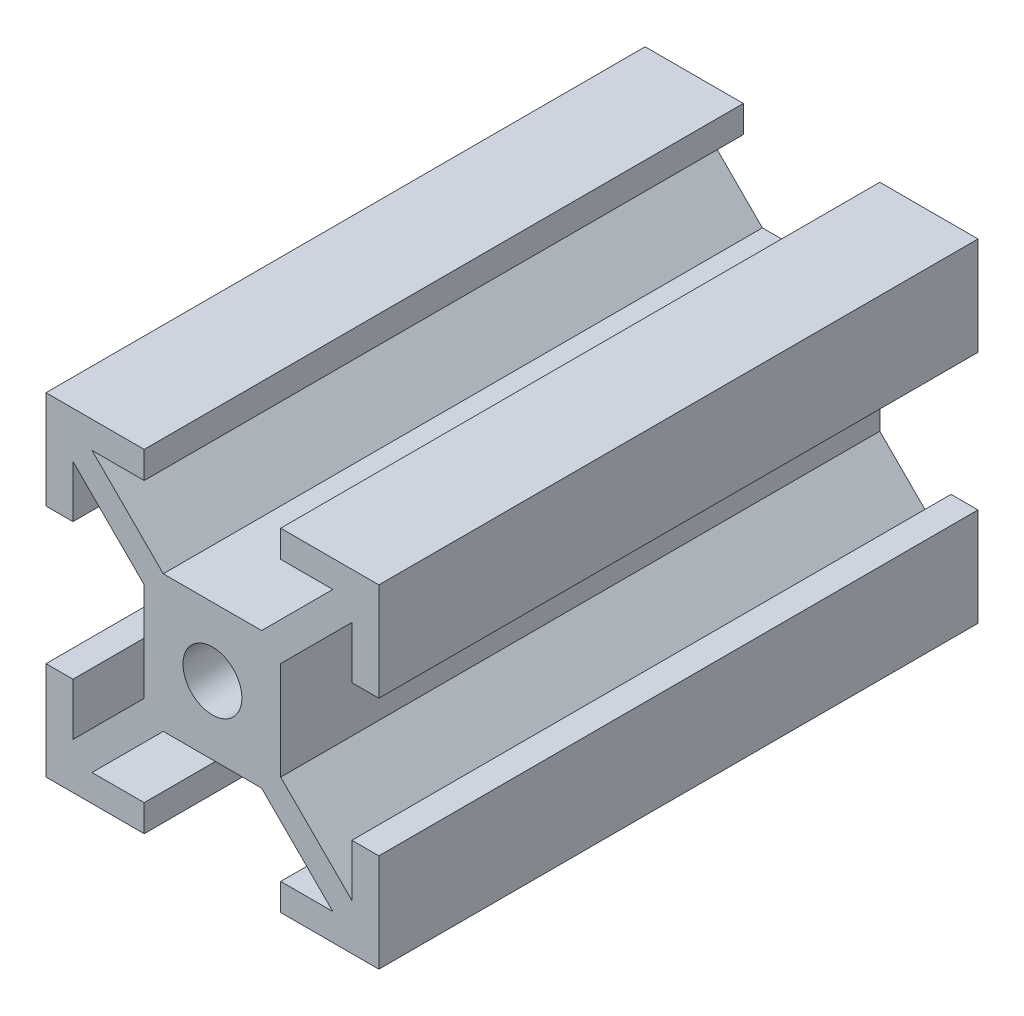
SolidWorks part; units mm, degrees
ref_plane "Front Plane" through (0, 0, 0) normal (0, 0, 1) x (1, 0, 0)
ref_plane "Top Plane" through (0, 0, 0) normal (0, 1, 0) x (1, 0, 0)
ref_plane "Right Plane" through (0, 0, 0) normal (1, 0, 0) x (0, 0, -1)
sketch "Sketch1" plane through (0, 0, 0) normal (0, 0, 1) x (1, 0, 0)
  line L0 (-8.38, 4.1) -> (-10, 4.1)
  line L1 (-2.9545, 4.1) -> (2.9545, 4.1)
  line L2 (-4.1, 2.9545) -> (-4.1, -2.9545)
  line L3 (-2.9545, -4.1) -> (2.9545, -4.1)
  line L4 (4.1, 2.9545) -> (4.1, -2.9545)
  line L5 (-4.1, 4.1) -> (4.1, -4.1) construction
  line L6 (-4.1, -4.1) -> (4.1, 4.1) construction
  line L7 (-10, 10) -> (-4.1, 10)
  line L8 (-10, 10) -> (-10, 4.1)
  line L9 (-10, -10) -> (-4.1, -10)
  line L10 (10, 10) -> (10, 4.1)
  line L11 (-10, 10) -> (10, -10) construction
  line L12 (-10, -10) -> (10, 10) construction
  line L13 (-7.2345, 8.38) -> (-4.1, 8.38)
  line L14 (-8.38, 7.2345) -> (-8.38, 4.1)
  line L15 (-7.2345, -8.38) -> (-4.1, -8.38)
  line L16 (8.38, 7.2345) -> (8.38, 4.1)
  line L17 (-8.38, 8.38) -> (8.38, -8.38) construction
  line L18 (-8.38, -8.38) -> (8.38, 8.38) construction
  line L19 (-4.1, 8.38) -> (-4.1, 10)
  line L20 (4.1, 10) -> (4.1, 8.38)
  line L21 (8.38, 4.1) -> (10, 4.1)
  line L22 (-8.38, -4.1) -> (-10, -4.1)
  line L23 (-4.1, -8.38) -> (-4.1, -10)
  line L24 (8.38, -4.1) -> (10, -4.1)
  line L25 (4.1, -8.38) -> (4.1, -10)
  line L26 (-5.464, 5.464) -> (-4.8912, 6.0368) construction
  line L27 (-4.1, 2.9545) -> (-8.38, 7.2345)
  line L28 (-2.9545, 4.1) -> (-7.2345, 8.38)
  line L29 (0, 11.3108) -> (0, -17.1823) construction
  line L30 (-16.7028, 0) -> (14.4032, 0) construction
  line L31 (-2.9545, -4.1) -> (-7.2345, -8.38)
  line L32 (-4.1, -2.9545) -> (-8.38, -7.2345)
  line L33 (2.9545, -4.1) -> (7.2345, -8.38)
  line L34 (4.1, -2.9545) -> (8.38, -7.2345)
  line L35 (4.1, 2.9545) -> (8.38, 7.2345)
  line L36 (2.9545, 4.1) -> (7.2345, 8.38)
  line L37 (4.1, 8.38) -> (7.2345, 8.38)
  line L38 (4.1, 10) -> (10, 10)
  line L39 (-8.38, -4.1) -> (-8.38, -7.2345)
  line L40 (-10, -4.1) -> (-10, -10)
  line L41 (8.38, -4.1) -> (8.38, -7.2345)
  line L42 (10, -4.1) -> (10, -10)
  line L43 (4.1, -8.38) -> (7.2345, -8.38)
  line L44 (4.1, -10) -> (10, -10)
  circle A0 centre (0, 0) radius 1.77
  point P0 (0, 0)
  point P6 (0, 0)
  dimension "D5" = 3.54
  dimension "D1" = 8.2
  dimension "D2" = 20
  dimension "D3" = 8.2
  dimension "D4" = 20
  dimension "D6" = 16.76
  dimension "D7" = 16.76
  dimension "D8" = 0.81
  dimension "D9" = 135
  dimension "D10" = 7.7696
  dimension "D11" = 5.0536
extrude "Boss-Extrude1" add sketch "Sketch1" along normal blind 36
